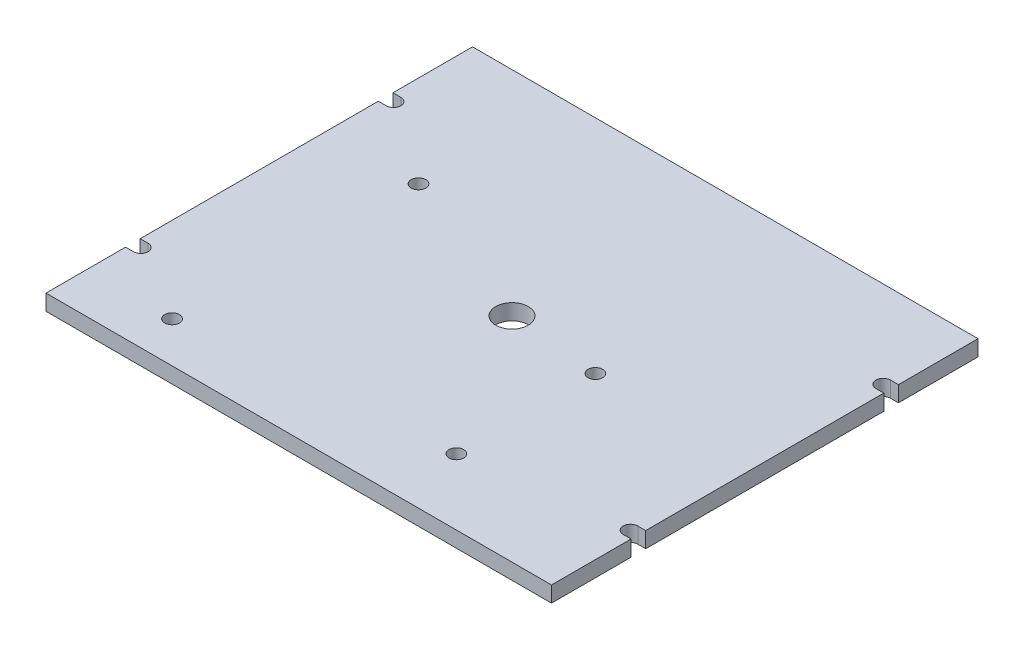
SolidWorks part; units mm, degrees
ref_plane "Front Plane" through (0, 0, 0) normal (0, 0, 1) x (1, 0, 0)
ref_plane "Top Plane" through (0, 0, 0) normal (0, 1, 0) x (1, 0, 0)
ref_plane "Right Plane" through (0, 0, 0) normal (1, 0, 0) x (0, 0, -1)
sketch "Sketch1" plane through (0, 0, 0) normal (0, 1, 0) x (1, 0, 0)
  line L1 (-50.8, -42.8625) -> (50.8, -42.8625)
  line L2 (-50.8, -42.8625) -> (-50.8, 42.8625)
  line L3 (-50.8, 42.8625) -> (50.8, 42.8625)
  line L4 (50.8, -42.8625) -> (50.8, 42.8625)
  line L5 (-50.8, -42.8625) -> (50.8, 42.8625) construction
  line L6 (-50.8, 42.8625) -> (50.8, -42.8625) construction
  point P0 (0, 0)
  dimension "D1" = 101.6
  dimension "D2" = 85.725
extrude "Boss-Extrude1" add sketch "Sketch1" along normal blind 3.175
hole_wizard "#4 Clearance Hole1" positions "Sketch2" profile "Sketch3" hole size "#4" standard "ANSI Inch" end condition through all
sketch "Sketch2" plane through (0, 0, 0) normal (0, -1, 0) x (-1, 0, 0)
  point P0 (-18.415, -1.6525)
  point P3 (-18.415, -29.5925)
  point P6 (33.655, -34.6725)
  point P9 (32.385, 13.5875)
sketch "Sketch3" plane through (18.415, 0, 1.6525) normal (1, 0, 0) x (0, 0, -1)
  line L0 (0, 0) -> (0, 3.175)
  line L1 (0, 3.175) -> (1.4732, 3.175)
  line L2 (1.4732, 3.175) -> (1.4732, 0)
  line L5 (1.4732, 0) -> (0, 0)
  line L11 (0, -6.35) -> (0, 107.95) construction
  dimension "Thru Hole Dia." = 2.9464
  dimension "Thru Hole Depth" = 3.175
sketch "Sketch4" plane through (0, 0, 0) normal (0, -1, 0) x (1, 0, 0)
  line L0 (50.8, -42.8625) -> (-50.8, 42.8625) construction
  line L1 (-50.8, 42.8625) -> (50.8, 42.8625) construction
  line L2 (49.2125, 41.275) -> (-49.2125, 41.275) construction
  line L3 (49.2125, 41.275) -> (49.2125, -41.275) construction
  line L4 (49.2125, -41.275) -> (-49.2125, -41.275) construction
  line L5 (-49.2125, 41.275) -> (-49.2125, -41.275) construction
  line L6 (49.2125, 41.275) -> (-49.2125, -41.275) construction
  line L7 (49.2125, -41.275) -> (-49.2125, 41.275) construction
  line L8 (50.8, 42.8625) -> (50.8, -42.8625) construction
  line L9 (49.2125, -26.8732) -> (50.8, -26.8732)
  line L10 (49.2125, -23.9268) -> (50.8, -23.9268)
  line L11 (50.8, -26.8732) -> (50.8, -23.9268)
  line L12 (49.2125, 26.8732) -> (50.8, 26.8732)
  line L13 (50.8, 23.9268) -> (50.8, 26.8732)
  line L14 (49.2125, 23.9268) -> (50.8, 23.9268)
  line L15 (0, 0) -> (0, 12.3904) construction
  line L16 (-49.2125, 26.8732) -> (-50.8, 26.8732)
  line L17 (-50.8, 23.9268) -> (-50.8, 26.8732)
  line L18 (-49.2125, 23.9268) -> (-50.8, 23.9268)
  line L19 (-49.2125, -23.9268) -> (-50.8, -23.9268)
  line L20 (-49.2125, -26.8732) -> (-50.8, -26.8732)
  line L21 (-50.8, -26.8732) -> (-50.8, -23.9268)
  arc A0 (49.2125, -23.9268) -> (49.2125, -26.8732) centre (49.2125, -25.4) ccw
  arc A1 (49.2125, 26.8732) -> (49.2125, 23.9268) centre (49.2125, 25.4) ccw
  arc A2 (-49.2125, 26.8732) -> (-49.2125, 23.9268) centre (-49.2125, 25.4) cw
  arc A3 (-49.2125, -23.9268) -> (-49.2125, -26.8732) centre (-49.2125, -25.4) cw
  point P2 (0, 0)
  point P16 (49.2125, 0)
  dimension "D3" = 2.9464
  dimension "D1" = 1.5875
  dimension "D2" = 1.5875
  dimension "D4" = 25.4
  dimension "D5" = 2
extrude "Cut-Extrude1" cut sketch "Sketch4" against normal through all
hole_wizard "1/4 Clearance Hole1" positions "Sketch7" profile "Sketch8" hole size "1/4" standard "ANSI Inch" end condition through all
sketch "Sketch7" plane through (0, 0, 0) normal (0, -1, 0) x (-1, 0, 0)
  point P0 (0, 0)
sketch "Sketch8" plane through (0, 0, 0) normal (1, 0, 0) x (0, 0, -1)
  line L0 (0, 0) -> (0, 3.175)
  line L1 (0, 3.175) -> (3.2639, 3.175)
  line L2 (3.2639, 3.175) -> (3.2639, 0)
  line L5 (3.2639, 0) -> (0, 0)
  line L11 (0, -6.35) -> (0, 107.95) construction
  dimension "Thru Hole Dia." = 6.5278
  dimension "Thru Hole Depth" = 3.175
